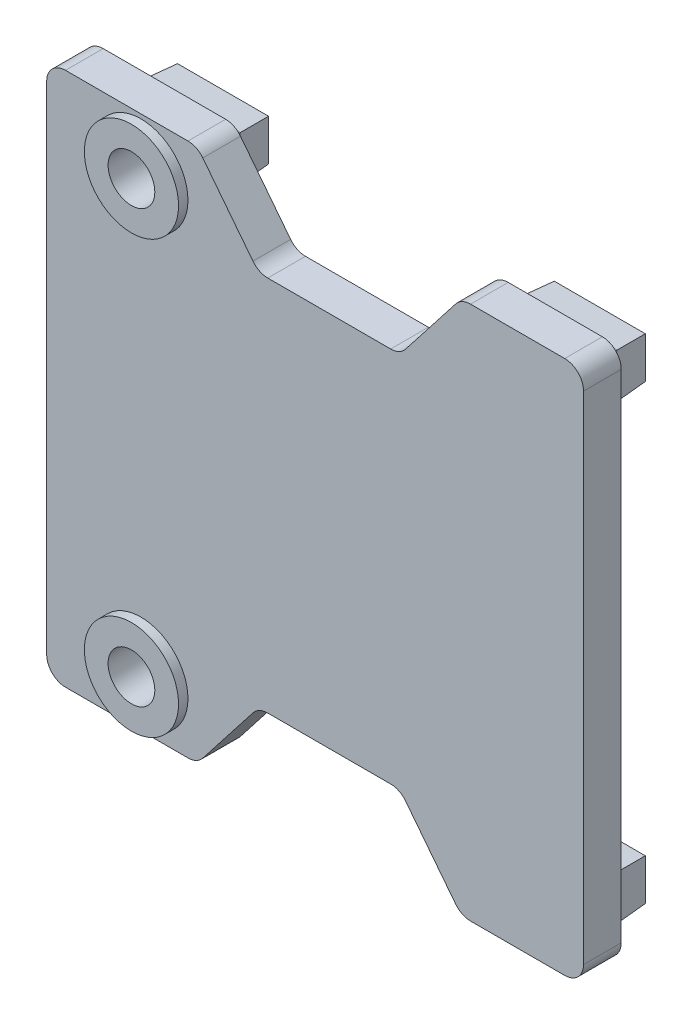
SolidWorks part; units mm, degrees
ref_plane "Front Plane" through (0, 0, 0) normal (0, 0, 1) x (1, 0, 0)
ref_plane "Top Plane" through (0, 0, 0) normal (0, 1, 0) x (1, 0, 0)
ref_plane "Right Plane" through (0, 0, 0) normal (1, 0, 0) x (0, 0, -1)
sketch "Sketch1" plane through (0, 0, 0) normal (0, 0, 1) x (1, 0, 0)
  line L0 (190.5, 35.0834) -> (-190.5, -35.0834) construction
  line L1 (190.5, -25.4) -> (-190.5, -25.4) construction
  line L2 (190.5, -25.4) -> (190.5, 25.4) construction
  line L3 (190.5, 25.4) -> (-190.5, 25.4) construction
  line L4 (-190.5, -25.4) -> (-190.5, 16.74) construction
  line L5 (190.5, -25.4) -> (-190.5, 25.4) construction
  line L6 (190.5, 25.4) -> (-190.5, -25.4) construction
  line L7 (-190.5, 20.09) -> (190.5, 20.09) construction
  line L8 (-184.15, 18.01) -> (-180.975, 18.01)
  line L9 (178.0459, 12.7) -> (-197.2145, 12.7) construction
  line L10 (-179.9737, 17.5212) -> (-176.5938, 13.1888)
  line L11 (-166.3062, 13.1888) -> (-162.9263, 17.5212)
  line L12 (-161.925, 18.01) -> (-155.575, 18.01)
  line L13 (-154.305, 16.74) -> (-154.305, 0)
  line L14 (0, 0) -> (-190.5, 0) construction
  line L15 (-154.305, 0) -> (-190.5, 0)
  line L16 (-190.5, 0) -> (-190.5, 16.74)
  line L17 (-175.5925, 12.7) -> (-167.3075, 12.7)
  line L18 (-184.15, 18.01) -> (-189.23, 18.01)
  line L19 (-155.575, 16.74) -> (-161.925, 16.74) construction
  line L20 (-155.575, 16.74) -> (-155.575, 13.74) construction
  line L21 (-155.575, 13.74) -> (-161.925, 13.74) construction
  line L22 (-161.925, 16.74) -> (-161.925, 13.74) construction
  line L23 (-155.575, 16.74) -> (-161.925, 13.74) construction
  line L24 (-155.575, 13.74) -> (-161.925, 16.74) construction
  line L25 (-190.5, 19.2281) -> (-190.5, 16.74) construction
  line L26 (-190.5, 16.74) -> (-190.5, 19.2281) construction
  line L27 (-180.975, 16.74) -> (-187.325, 16.74) construction
  line L28 (-180.975, 16.74) -> (-180.975, 13.74) construction
  line L29 (-180.975, 13.74) -> (-187.325, 13.74) construction
  line L30 (-187.325, 16.74) -> (-187.325, 13.74) construction
  line L31 (-180.975, 16.74) -> (-187.325, 13.74) construction
  line L32 (-180.975, 13.74) -> (-187.325, 16.74) construction
  line L33 (-190.5, 19.2281) -> (-190.5, 25.4) construction
  line L34 (-190.5, 16.74) -> (-190.5, 19.2281) construction
  circle A0 centre (-184.15, 14.5464) radius 5.5436 construction
  circle A1 centre (-184.15, 14.5464) radius 4.5 construction
  circle A2 centre (-184.15, 14.5464) radius 1.575
  circle A3 centre (-184.15, 14.5464) radius 3.175 construction
  arc A4 (-175.5925, 12.7) -> (-176.5938, 13.1888) centre (-175.5925, 13.97) cw
  arc A5 (-167.3075, 12.7) -> (-166.3062, 13.1888) centre (-167.3075, 13.97) ccw
  arc A6 (-162.9263, 17.5212) -> (-161.925, 18.01) centre (-161.925, 16.74) cw
  arc A7 (-154.305, 16.74) -> (-155.575, 18.01) centre (-155.575, 16.74) ccw
  arc A8 (-179.9737, 17.5212) -> (-180.975, 18.01) centre (-180.975, 16.74) ccw
  arc A9 (-189.23, 18.01) -> (-190.5, 16.74) centre (-189.23, 16.74) ccw
  point P0 (0, 0)
  point P8 (0, 0)
  point P27 (-158.75, 15.24)
  point P34 (-171.2683, 29.44)
  point P37 (-176.2125, 12.7)
  point P40 (-166.6875, 12.7)
  point P46 (-176.2125, 12.7)
  point P51 (-190.5, 18.01)
  point P52 (0, 0)
  point P53 (-167.5412, 20.09)
  point P54 (-184.15, 15.24)
  point P59 (0, 0)
  point P60 (0, 0)
  point P61 (-171.45, 12.7)
  point P62 (0, 0)
  point P63 (0, 0)
  dimension "D3" = 9
  dimension "D4" = 11.0871
  dimension "D6" = 3.15
  dimension "D7" = 6.35
  dimension "D14" = 1.27
  dimension "D1" = 50.8
  dimension "D2" = 5.31
  dimension "D5" = 6.35
  dimension "D8" = 9.525
  dimension "D9" = 19.05
  dimension "D10" = 3
  dimension "D11" = 6.35
  dimension "D12" = 15.24
  dimension "D13" = 31.75
  dimension "D15" = 6.35
  dimension "D16" = 6.35
  dimension "D17" = 3
  dimension "D18" = 381
  dimension "D21" = 12.7
extrude "Boss-Extrude1" add sketch "Sketch1" along normal blind 2.54
sketch "Sketch2" plane through (0, 0, 2.54) normal (0, 0, 1) x (1, 0, 0)
  circle A0 centre (-184.15, 14.5464) radius 1.575
  circle A1 centre (-184.15, 14.5464) radius 3.175
  circle A2 centre (-184.15, 14.5464) radius 1.575 construction
  dimension "D1" = 6.35
extrude "Boss-Extrude2" add sketch "Sketch2" along normal offset from surface (0.635 mm away) 3.175 up to face at (-171.8582, 13.7761, 0)
sketch "Sketch3" plane through (0, 0, 0) normal (0, 0, -1) x (-1, 0, 0)
  line L0 (0, 0) -> (197.0263, 0) construction
  line L1 (187.325, 13.74) -> (180.975, 13.74)
  line L2 (187.325, 13.74) -> (187.325, 16.74)
  line L3 (187.325, 16.74) -> (180.975, 16.74)
  line L4 (180.975, 13.74) -> (180.975, 16.74)
  line L5 (187.325, 13.74) -> (180.975, 16.74) construction
  line L6 (187.325, 16.74) -> (180.975, 13.74) construction
  line L7 (161.925, 13.74) -> (155.575, 13.74)
  line L8 (161.925, 13.74) -> (161.925, 16.74)
  line L9 (161.925, 16.74) -> (155.575, 16.74)
  line L10 (155.575, 13.74) -> (155.575, 16.74)
  line L11 (161.925, 13.74) -> (155.575, 16.74) construction
  line L12 (161.925, 16.74) -> (155.575, 13.74) construction
  line L13 (-190.5, 25.4) -> (190.5, -25.4) construction
  point P0 (184.15, 15.24)
  point P5 (158.75, 15.24)
  point P10 (0, 0)
  dimension "D1" = 6.35
  dimension "D2" = 3
  dimension "D3" = 15.24
  dimension "D4" = 25.4
  dimension "D5" = 6.35
extrude "Boss-Extrude3" add sketch "Sketch3" along normal blind 1
sketch "Sketch4" plane through (0, 0, -1) normal (0, 0, -1) x (-1, 0, 0)
  line L0 (180.975, 16.74) -> (180.975, 13.74) construction
  line L1 (180.975, 13.74) -> (187.325, 13.74) construction
  line L2 (187.325, 13.74) -> (187.325, 16.74) construction
  line L3 (187.325, 16.74) -> (180.975, 16.74) construction
  line L4 (155.575, 16.74) -> (155.575, 13.74) construction
  line L5 (155.575, 13.74) -> (161.925, 13.74) construction
  line L6 (161.925, 13.74) -> (161.925, 16.74) construction
  line L7 (161.925, 16.74) -> (155.575, 16.74) construction
  line L8 (180.975, 16.74) -> (180.975, 13.74)
  line L9 (180.975, 13.74) -> (187.325, 13.74)
  line L10 (187.325, 13.74) -> (187.325, 16.74)
  line L11 (187.325, 16.74) -> (180.975, 16.74)
  line L12 (155.575, 16.74) -> (155.575, 13.74)
  line L13 (155.575, 13.74) -> (161.925, 13.74)
  line L14 (161.925, 13.74) -> (161.925, 16.74)
  line L15 (161.925, 16.74) -> (155.575, 16.74)
extrude "Boss-Extrude4" add sketch "Sketch4" along normal offset from surface 3 draft 3
mirror "Mirror1" about plane through (0, 0, 0) normal (0, 1, 0) of bodies 105 102
